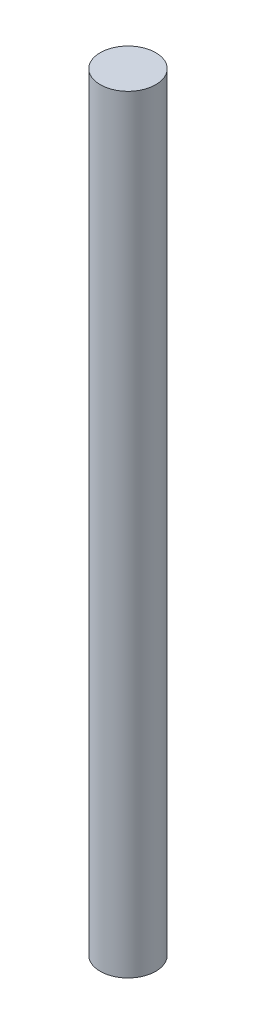
SolidWorks part; units mm, degrees
ref_plane "Спереди" through (0, 0, 0) normal (0, 0, 1) x (1, 0, 0)
ref_plane "Сверху" through (0, 0, 0) normal (0, 1, 0) x (1, 0, 0)
ref_plane "Справа" through (0, 0, 0) normal (1, 0, 0) x (0, 0, -1)
sketch "Sketch1" plane through (0, 0, 0) normal (0, 1, 0) x (1, 0, 0)
  circle A0 centre (0, 0) radius 3
  dimension "D1" = 6
extrude "Boss-Extrude1" add sketch "Sketch1" along normal blind 83
